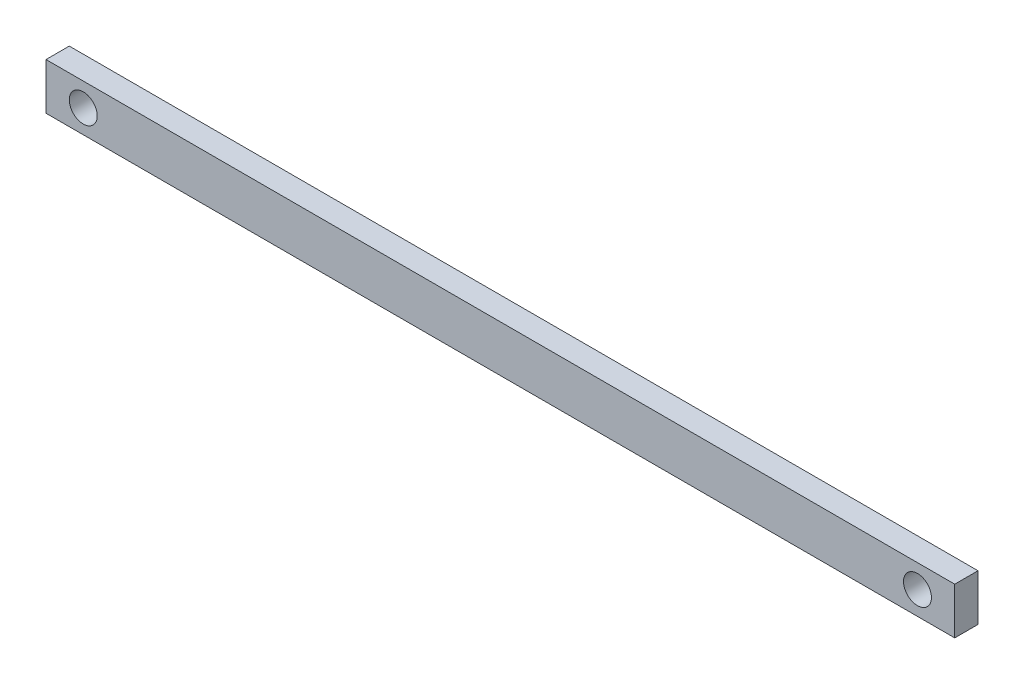
SolidWorks part; units mm, degrees
ref_plane "Front Plane" through (0, 0, 0) normal (0, 0, 1) x (1, 0, 0)
ref_plane "Top Plane" through (0, 0, 0) normal (0, 1, 0) x (1, 0, 0)
ref_plane "Right Plane" through (0, 0, 0) normal (1, 0, 0) x (0, 0, -1)
sketch "Sketch1" plane through (0, 0, 0) normal (0, 0, 1) x (1, 0, 0)
  line L0 (-280.6502, 0) -> (339.3909, 0) construction
  line L1 (0, 157.144) -> (0, -198.3128) construction
  line L3 (-244, 12.5) -> (244, 12.5)
  line L4 (-244, 12.5) -> (-244, -12.5)
  line L5 (-244, -12.5) -> (244, -12.5)
  line L6 (244, 12.5) -> (244, -12.5)
  circle A0 centre (-224, 0) radius 7.5
  circle A1 centre (224, 0) radius 7.5
  point P5 (0, 0)
  dimension "D3" = 15
  dimension "D4" = 15
  dimension "D1" = 488
  dimension "D2" = 25
  dimension "D5" = 224
  dimension "D6" = 224
extrude "Boss-Extrude1" add sketch "Sketch1" along normal blind 25
sketch "Sketch2" plane through (244, 0, 0) normal (1, 0, 0) x (0, 0, -1)
  line L0 (-34.5416, 0) -> (14.8246, 0) construction
  line L1 (0, 13.5398) -> (0, -14.0646) construction
  line L4 (0, 12.5) -> (-12.5, 12.5)
  line L5 (-25, 12.5) -> (0, 12.5) construction
  line L6 (-12.5, 12.5) -> (-12.5, -12.5)
  line L7 (-25, -12.5) -> (0, -12.5) construction
  line L8 (-12.5, -12.5) -> (0, -12.5)
  line L9 (0, -12.5) -> (0, 12.5)
extrude "Cut-Extrude1" cut sketch "Sketch2" against normal through all both and the other way through all
